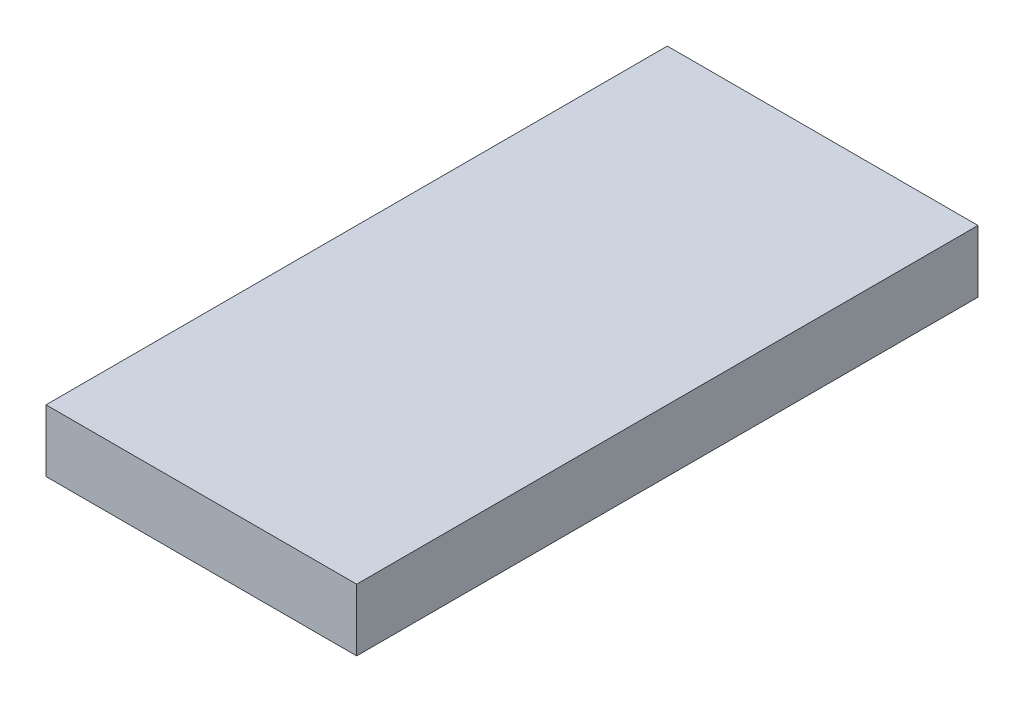
SolidWorks part; units mm, degrees
ref_plane "Front Plane" through (0, 0, 0) normal (0, 0, 1) x (1, 0, 0)
ref_plane "Top Plane" through (0, 0, 0) normal (0, 1, 0) x (1, 0, 0)
ref_plane "Right Plane" through (0, 0, 0) normal (1, 0, 0) x (0, 0, -1)
sketch "Sketch1" plane through (0, 0, 0) normal (0, 1, 0) x (1, 0, 0)
  line L0 (0, 0) -> (0, 120)
  line L1 (0, 120) -> (60, 120)
  line L2 (60, 120) -> (60, 0)
  line L3 (60, 0) -> (0, 0)
extrude "Boss-Extrude1" add sketch "Sketch1" along normal mid plane 12
ref_plane "Plane1" through (30, 0, 0) normal (1, 0, 0) x (0, 0, -1)
ref_plane "Plane2" through (0, 0, -60) normal (0, 0, 1) x (1, 0, 0)
